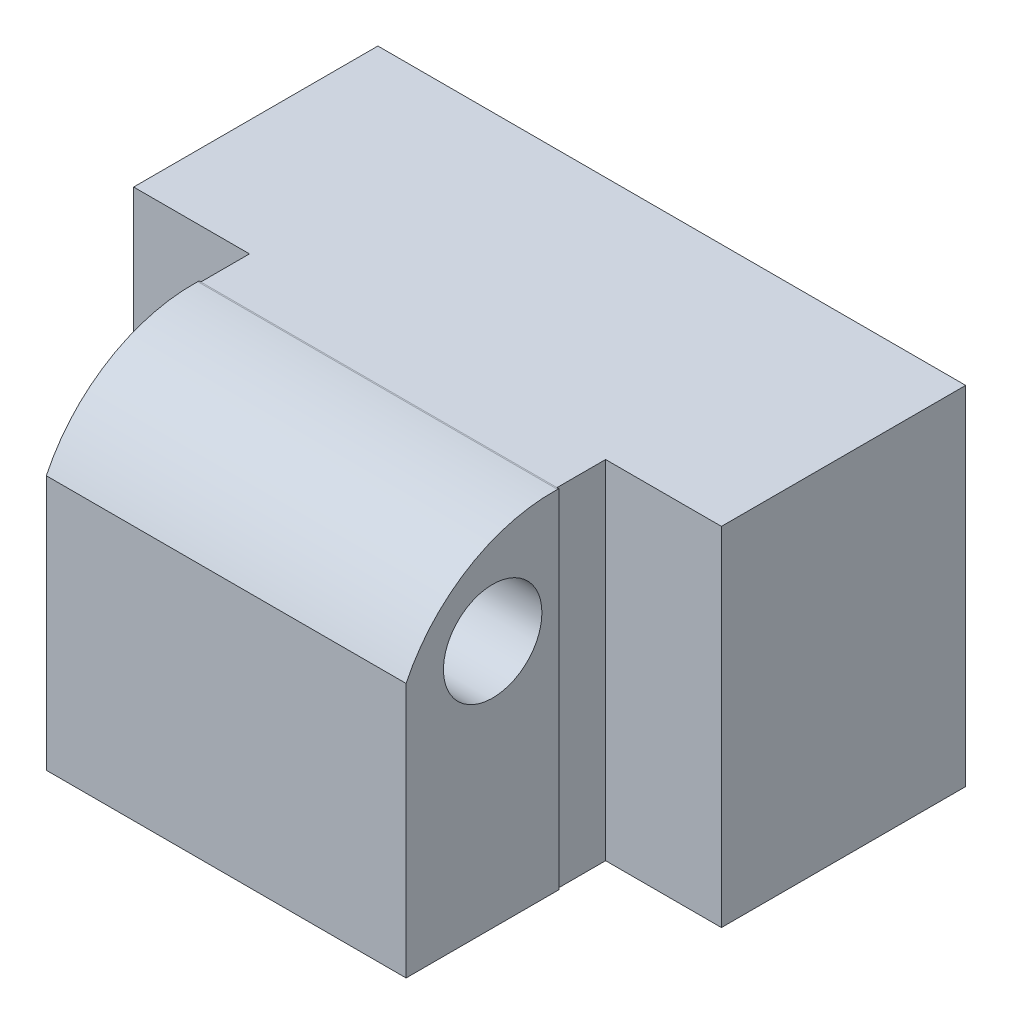
SolidWorks part; units mm, degrees
ref_plane "Front Plane" through (0, 0, 0) normal (0, 0, 1) x (1, 0, 0)
ref_plane "Top Plane" through (0, 0, 0) normal (0, 1, 0) x (1, 0, 0)
ref_plane "Right Plane" through (0, 0, 0) normal (1, 0, 0) x (0, 0, -1)
sketch "Sketch1" plane through (0, 0, 0) normal (0, 1, 0) x (1, 0, 0)
  line L0 (10.15, -65.2544) -> (6.15, -65.2544)
  line L1 (-10.15, -56.8193) -> (10.15, -56.8193)
  line L8 (6.15, -65.2544) -> (6.15, -66.9344)
  line L9 (6.15, -66.9344) -> (-6.15, -66.9344)
  line L10 (-6.15, -66.9344) -> (-6.15, -65.2544)
  line L11 (-6.15, -65.2544) -> (-10.15, -65.2544)
  line L12 (-10.15, -65.2544) -> (-10.15, -56.8193)
  line L13 (10.15, -65.2544) -> (10.15, -56.8193)
  dimension "D5" = 4
  dimension "D16" = 1.68
extrude "Boss-Extrude1" add sketch "Sketch1" along normal blind 12
sketch "Sketch2" plane through (0, 0, 0) normal (1, 0, 0) x (0, 0, -1)
  line L3 (-72.2073, 5.9997) -> (-72.2073, 8.8097)
  line L6 (-66.9773, 11.9997) -> (-66.9344, 12)
  line L7 (-66.9344, 12) -> (-66.9344, 0)
  line L8 (-66.9344, 0) -> (-72.2073, 0)
  line L9 (-72.2073, 0) -> (-72.2073, 5.9997)
  circle A1 centre (-69.2173, 8.5797) radius 1.7
  arc A3 (-66.9773, 11.9997) -> (-72.2073, 8.8097) centre (-67.1423, 6.3879) ccw
  dimension "D2" = 3.4
  dimension "D4" = 2.81
  dimension "D1" = 2.2829
extrude "Boss-Extrude2" add sketch "Sketch2" along normal mid plane 12.425
